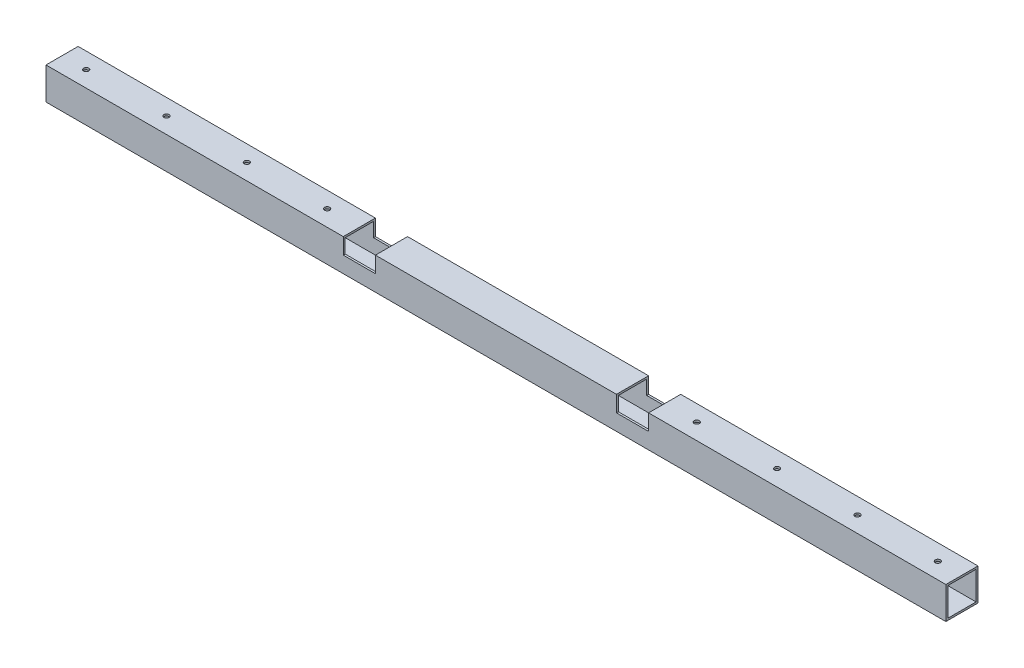
SolidWorks part; units mm, degrees
material "6061 合金"
ref_plane "前视基准面" through (0, 0, 0) normal (0, 0, 1) x (1, 0, 0)
ref_plane "上视基准面" through (0, 0, 0) normal (0, 1, 0) x (1, 0, 0)
ref_plane "右视基准面" through (0, 0, 0) normal (1, 0, 0) x (0, 0, -1)
sketch "草图1" plane through (0, 0, 0) normal (1, 0, 0) x (0, 0, -1)
  line L0 (-10, 10) -> (-10, -10)
  line L1 (-8.8, 8.8) -> (8.8, 8.8)
  line L2 (-8.8, 8.8) -> (-8.8, -8.8)
  line L3 (-8.8, -8.8) -> (8.8, -8.8)
  line L4 (8.8, 8.8) -> (8.8, -8.8)
  line L5 (-8.8, 8.8) -> (8.8, -8.8) construction
  line L6 (-8.8, -8.8) -> (8.8, 8.8) construction
  line L7 (-10, -10) -> (10, -10)
  line L8 (10, 10) -> (10, -10)
  line L9 (-10, 10) -> (10, 10)
  point P0 (0, 0)
  dimension "D1" = 1.2
  dimension "D2" = 20
  dimension "D3" = 20
extrude "凸台-拉伸1" add sketch "草图1" along normal mid plane 560
sketch "草图2" plane through (0, 0, -10) normal (0, 0, -1) x (-1, 0, 0)
  line L0 (0, 113.7589) -> (0, -114.3891) construction
  line L2 (-95, 10) -> (-75, 10)
  line L3 (-95, 10) -> (-95, 0)
  line L4 (-95, 0) -> (-75, 0)
  line L5 (-75, 10) -> (-75, 0)
  line L6 (-95, 10) -> (-75, 0) construction
  line L7 (-95, 0) -> (-75, 10) construction
  line L8 (-280, -10) -> (-280, 10) construction
  line L9 (95, 0) -> (75, 0)
  line L10 (75, 10) -> (75, 0)
  line L11 (95, 10) -> (75, 10)
  line L12 (95, 10) -> (95, 0)
  line L13 (-280, 10) -> (280, 10) construction
  point P3 (-85, 5)
  dimension "D1" = 20
  dimension "D2" = 185
  dimension "D3" = 10
extrude "切除-拉伸1" cut sketch "草图2" against normal through all
sketch "草图3" plane through (0, 10, 0) normal (0, 1, 0) x (1, 0, 0)
  line L0 (280, 0) -> (-280, 0) construction
  line L1 (280, 10) -> (280, -10) construction
  line L2 (-280, 10) -> (-280, -10) construction
  line L3 (0, -81.1519) -> (0, 80.1636) construction
  line L5 (95, -10) -> (75, -10) construction
  line L6 (95, -10) -> (75, -10) construction
  line L7 (85, -10) -> (85, 15.9167) construction
  circle A1 centre (115, 0) radius 1.6
  circle A2 centre (165, 0) radius 1.6
  circle A3 centre (265, 0) radius 1.6
  circle A4 centre (215, 0) radius 1.6
  circle A5 centre (-215, 0) radius 1.6
  circle A6 centre (-265, 0) radius 1.6
  circle A8 centre (-115, 0) radius 1.6
  circle A10 centre (85, 0) radius 1.6 construction
  circle A11 centre (-85, 0) radius 1.6 construction
  circle A13 centre (-165, 0) radius 1.6
  circle A14 centre (70, 0) radius 1.6 construction
  circle A15 centre (-70, 0) radius 1.6 construction
  circle A16 centre (40, 0) radius 1.6 construction
  circle A17 centre (-40, 0) radius 1.6 construction
  dimension "D1" = 3.2
  dimension "D7" = 3.2
  dimension "D8" = 30
  dimension "D9" = 50
  dimension "D5" = 15
  dimension "D2" = 50
  dimension "D3" = 50
  dimension "D4" = 15
  dimension "D6" = 50
extrude "切除-拉伸2" cut sketch "草图3" against normal through all
sketch "草图4" plane through (0, -10, 0) normal (0, -1, 0) x (1, 0, 0)
  line L0 (265, 0) -> (-77.0015, 0) construction
  line L1 (0, 113.1654) -> (0, -125.2139) construction
  circle A0 centre (240, 0) radius 2.5
  circle A1 centre (-240, 0) radius 2.5
  circle A2 centre (190, 0) radius 2.5
  circle A3 centre (140, 0) radius 2.5
  circle A4 centre (-140, 0) radius 2.5
  circle A5 centre (-190, 0) radius 2.5
  dimension "D1" = 5
  dimension "D3" = 50
  dimension "D2" = 25
  dimension "D4" = 50
extrude "切除-拉伸3" cut sketch "草图4" against normal up to next
